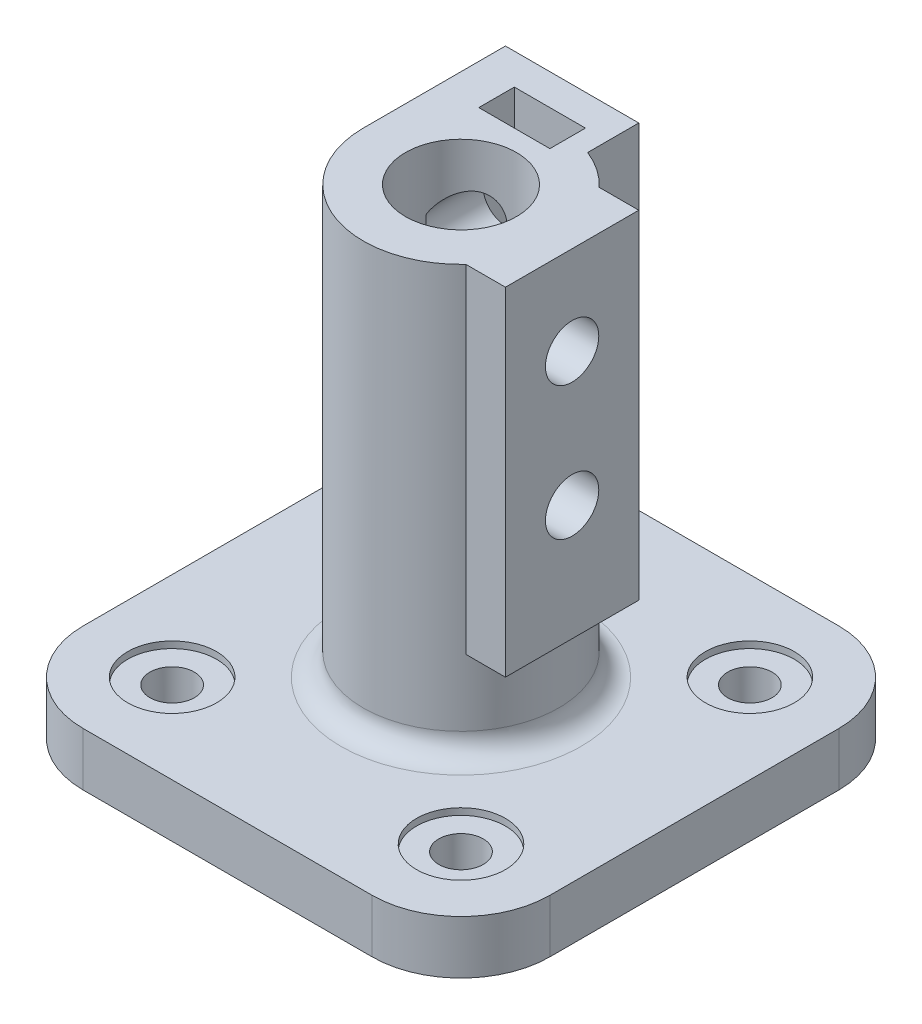
SolidWorks part; units mm, degrees
ref_plane "Front Plane" through (0, 0, 0) normal (0, 0, 1) x (1, 0, 0)
ref_plane "Top Plane" through (0, 0, 0) normal (0, 1, 0) x (1, 0, 0)
ref_plane "Right Plane" through (0, 0, 0) normal (1, 0, 0) x (0, 0, -1)
sketch "Sketch1" plane through (0, 0, 0) normal (0, 1, 0) x (1, 0, 0)
  line L1 (-32.5, 52.5) -> (32.5, 52.5)
  line L2 (-52.5, 32.5) -> (-52.5, -32.5)
  line L3 (-32.5, -52.5) -> (32.5, -52.5)
  line L4 (52.5, 32.5) -> (52.5, -32.5)
  arc A0 (-32.5, 52.5) -> (-52.5, 32.5) centre (-32.5, 32.5) ccw
  arc A1 (-32.5, -52.5) -> (-52.5, -32.5) centre (-32.5, -32.5) cw
  arc A2 (52.5, -32.5) -> (32.5, -52.5) centre (32.5, -32.5) cw
  arc A3 (52.5, 32.5) -> (32.5, 52.5) centre (32.5, 32.5) ccw
  point P0 (0, 0)
  point P10 (-52.5, 52.5)
  point P17 (52.5, 52.5)
  dimension "D5" = 20
  dimension "D6" = 20
  dimension "D7" = 20
  dimension "D8" = 20
  dimension "D1" = 105
  dimension "D2" = 52.5
  dimension "D3" = 105
  dimension "D4" = 52.5
extrude "Boss-Extrude2" add sketch "Sketch1" along normal blind 12
sketch "Sketch2" plane through (0, 12, 0) normal (0, 1, 0) x (1, 0, 0)
  circle A1 centre (-32.5, 32.5) radius 5
  circle A2 centre (32.5, 32.5) radius 5
  circle A3 centre (32.5, -32.5) radius 5
  circle A4 centre (-32.5, -32.5) radius 5
  dimension "D1" = 10
extrude "Cut-Extrude1" cut sketch "Sketch2" against normal blind 29
sketch "Sketch3" plane through (0, 12, 0) normal (0, 1, 0) x (1, 0, 0)
  circle A0 centre (-32.5, 32.5) radius 10
  circle A1 centre (32.5, 32.5) radius 10
  circle A3 centre (-32.5, -32.5) radius 10
  circle A4 centre (32.5, -32.5) radius 10
  dimension "D1" = 20
extrude "Cut-Extrude3" cut sketch "Sketch3" against normal blind 1.5 contours A1 | A0 | A4 | A3
sketch "Sketch4" plane through (0, 12, 0) normal (0, 1, 0) x (1, 0, 0)
  circle A0 centre (0, 0) radius 22
  circle A1 centre (0, 0) radius 12.5
  dimension "D1" = 44
  dimension "D2" = 25
extrude "Boss-Extrude3" add sketch "Sketch4" along normal blind 96
sketch "Sketch5" plane through (0, 108, 0) normal (0, 1, 0) x (1, 0, 0)
  line L1 (25, 15) -> (25, -15)
  line L3 (16.0935, -15) -> (25, -15)
  line L4 (16.0935, 15) -> (25, 15)
  arc A3 (16.0935, -15) -> (16.0935, 15) centre (0, 0) ccw
  circle A4 centre (0, 0) radius 22 construction
  point P7 (25, 22)
  point P8 (25, -22)
  point P12 (0, -15)
  point P14 (0, 15)
  dimension "D1" = 22
  dimension "D2" = 16.0935
  dimension "D3" = 25
extrude "Boss-Extrude4" add sketch "Sketch5" against normal blind 76
sketch "Sketch6" plane through (0, 108, 0) normal (0, 1, 0) x (1, 0, 0)
  line L2 (8, 20.4939) -> (8, 32)
  line L4 (-22, 0) -> (-22, 32)
  line L5 (-22, 20.4939) -> (-22, 52.5) construction
  line L7 (8, 32) -> (-22, 32)
  line L10 (8, 20.4939) -> (8, 52.5) construction
  arc A2 (8, 20.4939) -> (-22, 0) centre (0, 0) ccw
  point P22 (22, 32)
  dimension "D2" = 30
extrude "Boss-Extrude5" add sketch "Sketch6" against normal blind 57
sketch "Sketch7" plane through (0, 108, 0) normal (0, 1, 0) x (1, 0, 0)
  line L0 (-22, 32) -> (-22, 0) construction
  line L2 (3, 25) -> (-13, 25)
  line L5 (3, 25) -> (3, 17)
  line L6 (-13, 25) -> (-13, 17)
  line L7 (3, 17) -> (-13, 17)
  line L9 (25, 25) -> (-22, 25) construction
  line L10 (-13, 32) -> (-13, 0) construction
  line L11 (3, 32) -> (3, 0) construction
  line L12 (25, 17) -> (-22, 17) construction
  dimension "D1" = 9
  dimension "D2" = 32
  dimension "D6" = 47
  dimension "D3" = 16
  dimension "D4" = 8
extrude "Cut-Extrude4" cut sketch "Sketch7" against normal blind 50
sketch "Sketch8" plane through (25, 0, 0) normal (1, 0, 0) x (0, 0, -1)
  line L0 (-15, 108) -> (15, 108) construction
  line L1 (-15, 32) -> (-15, 108) construction
  circle A0 centre (0, 88) radius 6
  circle A1 centre (0, 58) radius 6
  point P4 (0, 0)
  dimension "D1" = 12
  dimension "D2" = 12
  dimension "D3" = 20
  dimension "D4" = 30
  dimension "D5" = 15
  dimension "D6" = 30
extrude "Cut-Extrude5" cut sketch "Sketch8" against normal blind 20
sketch "Sketch9" plane through (0, 0, -32) normal (0, 0, -1) x (-1, 0, 0)
  line L0 (-8, 108) -> (22, 108) construction
  line L1 (22, 51) -> (22, 108) construction
  circle A0 centre (7, 93) radius 5
  circle A1 centre (7, 71) radius 5
  point P8 (0.4518, 79.8302)
  point P9 (0, 0)
  dimension "D1" = 10
  dimension "D2" = 10
  dimension "D3" = 15
  dimension "D4" = 22
  dimension "D5" = 15
  dimension "D6" = 15
extrude "Cut-Extrude7" cut sketch "Sketch9" against normal blind 28 contours A1 | A0
fillet "Fillet1" radius 5 1 edges at (0, 12, 22)
